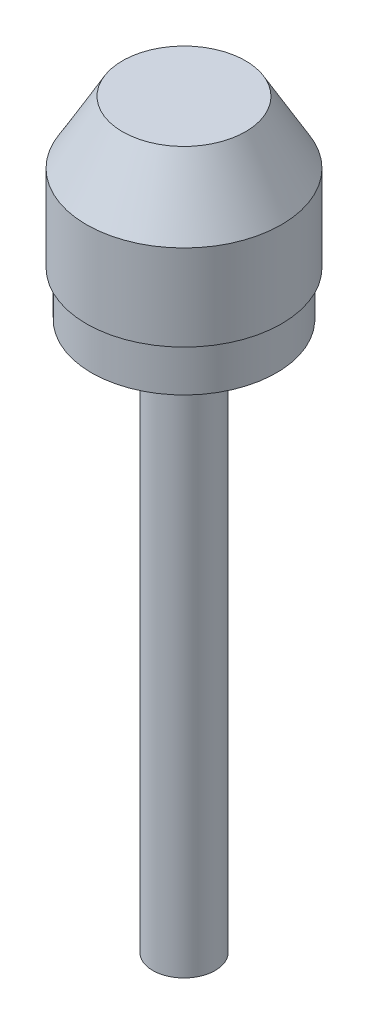
SolidWorks part; units mm, degrees
material "合金钢"
ref_plane "前视基准面" through (0, 0, 0) normal (0, 0, 1) x (1, 0, 0)
ref_plane "上视基准面" through (0, 0, 0) normal (0, 1, 0) x (1, 0, 0)
ref_plane "右视基准面" through (0, 0, 0) normal (1, 0, 0) x (0, 0, -1)
sketch "草图1" plane through (0, 0, 0) normal (0, 1, 0) x (1, 0, 0)
  circle A0 centre (0, 0) radius 2
  dimension "D1" = 4
extrude "凸台-拉伸1" add sketch "草图1" along normal blind 35
sketch "草图2" plane through (0, 35, 0) normal (0, 1, 0) x (1, 0, 0)
  circle A0 centre (0, 0) radius 5.925
  dimension "D1" = 11.85
extrude "凸台-拉伸2" add sketch "草图2" along normal blind 3
sketch "草图3" plane through (0, 38, 0) normal (0, 1, 0) x (1, 0, 0)
  circle A0 centre (0, 0) radius 6.25
  dimension "D1" = 12.5
extrude "凸台-拉伸3" add sketch "草图3" along normal blind 9.5
chamfer "倒角1" distance 4 angle 30 1 edges at (0, 47.5, 6.25)
chamfer "倒角2" distance 0.2 angle 30 1 edges at (0, 35, 5.925)
